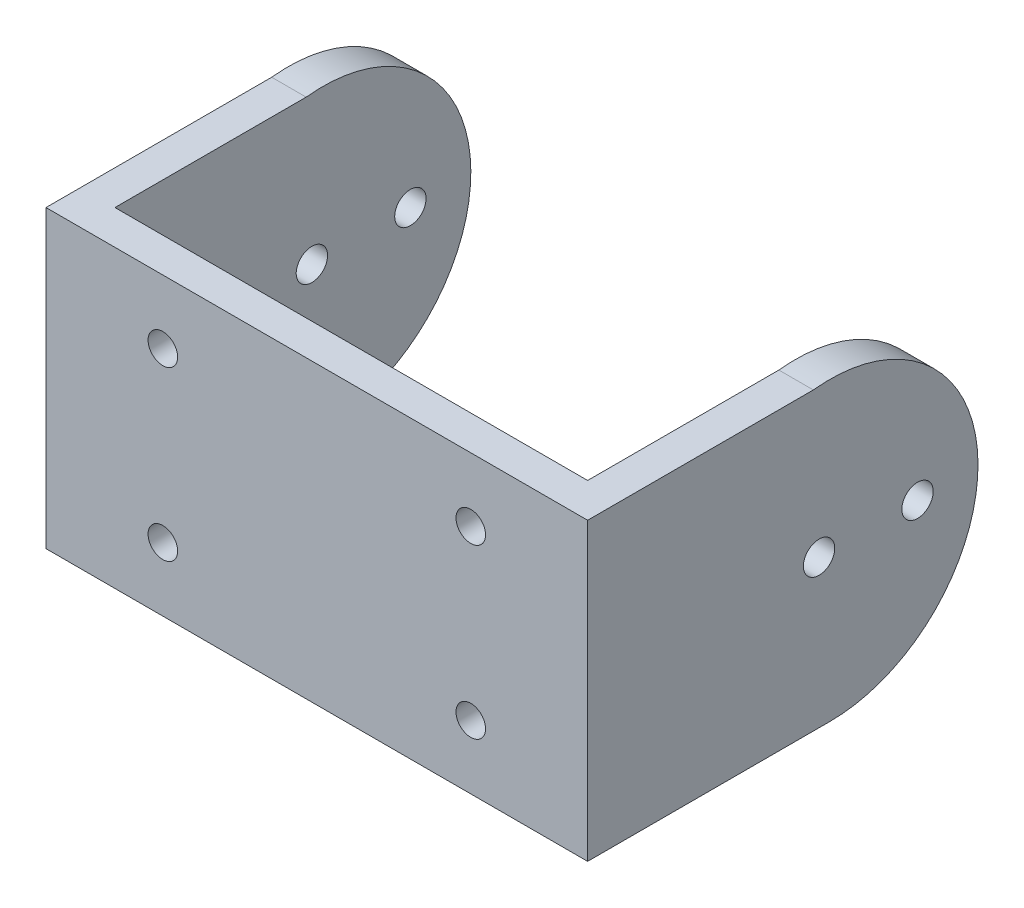
SolidWorks part; units mm, degrees
ref_plane "前视基准面" through (0, 0, 0) normal (0, 0, 1) x (1, 0, 0)
ref_plane "上视基准面" through (0, 0, 0) normal (0, 1, 0) x (1, 0, 0)
ref_plane "右视基准面" through (0, 0, 0) normal (1, 0, 0) x (0, 0, -1)
sketch "草图1" plane through (0, 0, 0) normal (0, 0, 1) x (1, 0, 0)
  line L0 (-33.0551, 0) -> (35.9054, 0) construction
  line L1 (27.5, -15) -> (-27.5, -15)
  line L2 (27.5, -15) -> (27.5, 15)
  line L3 (27.5, 15) -> (-27.5, 15)
  line L4 (-27.5, -15) -> (-27.5, 15)
  line L5 (27.5, -15) -> (-27.5, 15) construction
  line L6 (27.5, 15) -> (-27.5, -15) construction
  line L7 (0, 20.0988) -> (0, -17.0719) construction
  circle A0 centre (15.6347, 8.528) radius 1.5
  circle A1 centre (-15.6347, 8.528) radius 1.5
  circle A2 centre (15.6347, -8.528) radius 1.5
  circle A3 centre (-15.6347, -8.528) radius 1.5
  point P0 (0, 0)
  dimension "D3" = 3
  dimension "D1" = 30
  dimension "D2" = 55
extrude "凸台-拉伸1" add sketch "草图1" along normal blind 3.5
ref_plane "基准面1" through (27.5, 0, 0) normal (1, 0, 0) x (0, 0, -1)
sketch "草图2" plane through (27.5, 0, 0) normal (1, 0, 0) x (0, 0, -1)
  line L0 (0, 15) -> (0, -15)
  line L1 (0, -15) -> (0, 15) construction
  line L2 (0, -15) -> (21, -15)
  line L4 (19.4198, 15) -> (0, 15)
  arc A0 (19.4198, 15) -> (21, -15) centre (21.093, 0.0465) cw
  circle A2 centre (20, 0) radius 1.5927
  circle A3 centre (20, 0) radius 10 construction
  circle A15 centre (30, 0) radius 1.5927
  dimension "D7" = 20
extrude "凸台-拉伸2" add sketch "草图2" against normal blind 3.5
mirror "镜向1" about plane through (0, 0, 0) normal (1, 0, 0) of "凸台-拉伸2"
